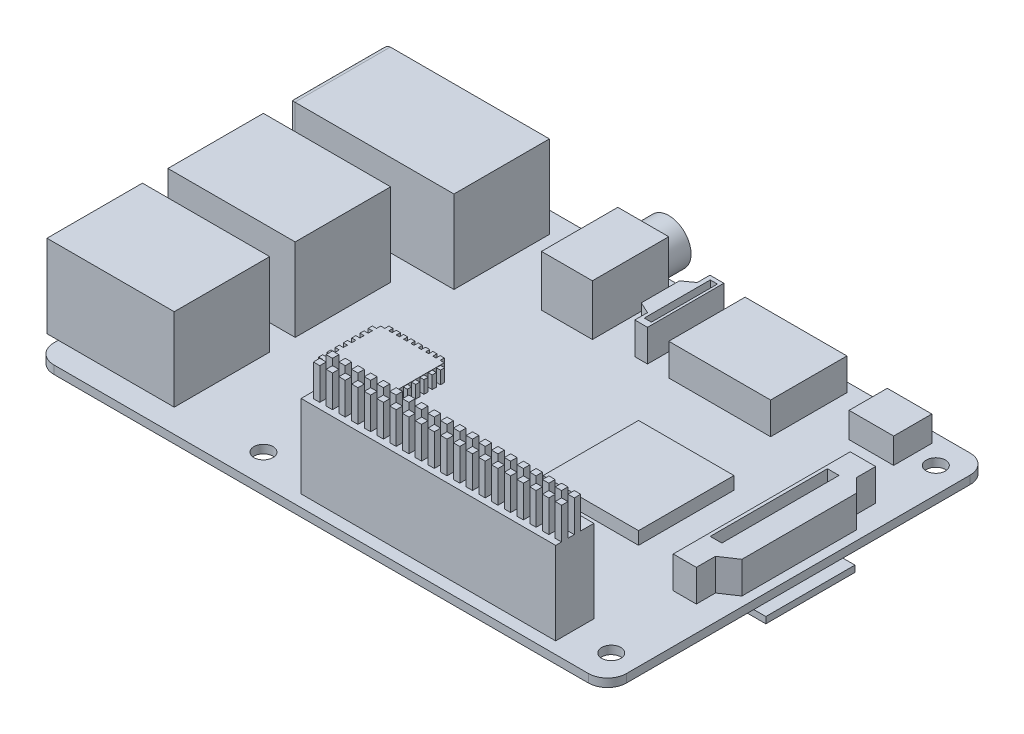
SolidWorks part; units mm, degrees
ref_plane "Front Plane" through (0, 0, 0) normal (0, 0, 1) x (1, 0, 0)
ref_plane "Top Plane" through (0, 0, 0) normal (0, 1, 0) x (1, 0, 0)
ref_plane "Right Plane" through (0, 0, 0) normal (1, 0, 0) x (0, 0, -1)
sketch "Sketch1" plane through (0, 0, 0) normal (0, 1, 0) x (1, 0, 0)
  line L1 (3, 0) -> (87, 0)
  line L2 (0, -3) -> (0, -57)
  line L3 (3, -60) -> (87, -60)
  line L4 (90, -3) -> (90, -57)
  line L6 (90, -18.75) -> (90, -31.25)
  arc A0 (87, 0) -> (90, -3) centre (87, -3) cw
  arc A1 (3, 0) -> (0, -3) centre (3, -3) ccw
  arc A2 (0, -57) -> (3, -60) centre (3, -57) ccw
  arc A3 (87, -60) -> (90, -57) centre (87, -57) ccw
  circle A4 centre (86, -55.4) radius 1.5
  circle A5 centre (86, -4.3927) radius 1.5
  circle A6 centre (31.3402, -55.4) radius 1.5
  circle A8 centre (31.3402, -4.3927) radius 1.5
  point P7 (90, 0)
  point P10 (0, 0)
  point P13 (0, -60)
  dimension "D3" = 3
  dimension "D4" = 3
  dimension "D5" = 1.6
  dimension "D6" = 4
  dimension "D7" = 4
  dimension "D8" = 3
  dimension "D1" = 90
  dimension "D2" = 60
extrude "Boss-Extrude3" add sketch "Sketch1" along normal blind 1.3 contours L3 A3 L4 A0 L1 A1 L2 A2
sketch "Sketch3" plane through (0, 0, 0) normal (0, -1, 0) x (1, 0, 0)
  line L6 (91.8941, 37) -> (71.8941, 37)
  line L7 (91.8941, 37) -> (91.8941, 23)
  line L8 (91.8941, 23) -> (71.8941, 23)
  line L9 (71.8941, 37) -> (71.8941, 23)
  arc A0 (87, 0) -> (90, 3) centre (87, 3) ccw construction
  arc A1 (90, 57) -> (87, 60) centre (87, 57) ccw construction
  dimension "D4" = 20
  dimension "D1" = 14
  dimension "D2" = 20
  dimension "2.1" = 20
extrude "Boss-Extrude4" add sketch "Sketch3" along normal blind 1
sketch "Sketch5" plane through (0, 1.3, 0) normal (0, 1, 0) x (1, 0, 0)
  line L1 (79.9977, -52.1364) -> (39.9977, -52.1364)
  line L2 (79.9977, -52.1364) -> (79.9977, -58.1364)
  line L3 (79.9977, -58.1364) -> (39.9977, -58.1364)
  line L4 (39.9977, -52.1364) -> (39.9977, -58.1364)
  dimension "D1" = 40
  dimension "D2" = 6
extrude "Boss-Extrude6" add sketch "Sketch5" along normal blind 13 contours L2 L3 L4 L1
sketch "Sketch9" plane through (0, 1.3, 0) normal (0, 1, 0) x (1, 0, 0)
  line L1 (18.2207, -41.3014) -> (-1.7793, -41.3014)
  line L2 (18.2207, -41.3014) -> (18.2207, -56.3014)
  line L3 (18.2207, -56.3014) -> (-1.7793, -56.3014)
  line L4 (-1.7793, -41.3014) -> (-1.7793, -56.3014)
  dimension "D1" = 15
  dimension "D2" = 20
extrude "Boss-Extrude7" add sketch "Sketch9" along normal blind 13
sketch "Sketch10" plane through (0, 1.3, 0) normal (0, 1, 0) x (1, 0, 0)
  line L1 (18.2251, -22.3014) -> (-1.7749, -22.3014)
  line L2 (18.2251, -22.3014) -> (18.2251, -37.3014)
  line L3 (18.2251, -37.3014) -> (-1.7749, -37.3014)
  line L4 (-1.7749, -22.3014) -> (-1.7749, -37.3014)
  dimension "D1" = 15
  dimension "D2" = 20
  dimension "D3" = 4
extrude "Boss-Extrude8" add sketch "Sketch10" along normal blind 13
sketch "Sketch12" plane through (0, 1.3, 0) normal (0, 1, 0) x (1, 0, 0)
  line L1 (24.1806, -3.3017) -> (-1.8194, -3.3017)
  line L2 (24.1806, -3.3017) -> (24.1806, -18.3017)
  line L3 (24.1806, -18.3017) -> (-1.8194, -18.3017)
  line L4 (-1.8194, -3.3017) -> (-1.8194, -18.3017)
  dimension "D1" = 15
  dimension "D2" = 26
  dimension "D3" = 4
extrude "Boss-Extrude9" add sketch "Sketch12" along normal blind 13
sketch "Sketch13" plane through (0, 1.3, 0) normal (0, 1, 0) x (1, 0, 0)
  line L1 (35.3901, -31.0333) -> (25.3901, -31.0333)
  line L2 (35.3901, -31.0333) -> (35.3901, -41.0333)
  line L3 (35.3901, -41.0333) -> (25.3901, -41.0333)
  line L4 (25.3901, -31.0333) -> (25.3901, -41.0333)
  dimension "D1" = 10
  dimension "D2" = 10
extrude "Boss-Extrude10" add sketch "Sketch13" along normal blind 2
sketch "Sketch14" plane through (0, 1.3, 0) normal (0, 1, 0) x (1, 0, 0)
  line L1 (73.5027, -23.6167) -> (58.5027, -23.6167)
  line L2 (73.5027, -23.6167) -> (73.5027, -38.6167)
  line L3 (73.5027, -38.6167) -> (58.5027, -38.6167)
  line L4 (58.5027, -23.6167) -> (58.5027, -38.6167)
  dimension "D1" = 15
  dimension "D2" = 15
extrude "Boss-Extrude11" add sketch "Sketch14" along normal blind 2
sketch "Sketch15" plane through (0, 1.3, 0) normal (0, 1, 0) x (1, 0, 0)
  line L1 (41.8681, -2.2375) -> (33.8681, -2.2375)
  line L2 (41.8681, -2.2375) -> (41.8681, -14.2375)
  line L3 (41.8681, -14.2375) -> (33.8681, -14.2375)
  line L4 (33.8681, -2.2375) -> (33.8681, -14.2375)
  dimension "D1" = 8
  dimension "D2" = 12
extrude "Boss-Extrude12" add sketch "Sketch15" along normal blind 8
sketch "Sketch16" plane through (0, 0, 2.2375) normal (0, 0, -1) x (-1, 0, 0)
  circle A0 centre (-37.8804, 4.69) radius 3.5
extrude "Boss-Extrude13" add sketch "Sketch16" along normal blind 4
sketch "Sketch17" plane through (0, 1.3, 0) normal (0, 1, 0) x (1, 0, 0)
  line L1 (69.1, -1.4635) -> (53.1, -1.4635)
  line L2 (69.1, -1.4635) -> (69.1, -13.4635)
  line L3 (69.1, -13.4635) -> (53.1, -13.4635)
  line L4 (53.1, -1.4635) -> (53.1, -13.4635)
  dimension "D1" = 16
  dimension "D2" = 12
extrude "Boss-Extrude15" add sketch "Sketch17" along normal blind 5
sketch "Sketch18" plane through (0, 1.3, 0) normal (0, 1, 0) x (1, 0, 0)
  line L1 (82.6732, -1.6952) -> (75.6732, -1.6952)
  line L2 (82.6732, -1.6952) -> (82.6732, -7.6952)
  line L3 (82.6732, -7.6952) -> (75.6732, -7.6952)
  line L4 (75.6732, -1.6952) -> (75.6732, -7.6952)
  dimension "D1" = 6
  dimension "D2" = 7
extrude "Boss-Extrude16" add sketch "Sketch18" along normal blind 4
fillet "Fillet1" radius 1 4 edges at (-1.8194, 7.8, 3.3017) (-1.8194, 14.3, 10.8017) (-1.8194, 7.8, 18.3017) (-1.8194, 1.3, 10.8017)
sketch "Sketch23" plane through (-1.8194, 0, 0) normal (-1, 0, 0) x (0, 0, 1)
  line L0 (8.563, 2.79) -> (13.2677, 2.79)
  line L1 (13.2677, 2.79) -> (13.2677, 4.6719)
  line L2 (13.2677, 4.6719) -> (13.2412, 5.2201)
  line L3 (13.2412, 5.2201) -> (15.1231, 5.2201)
  line L4 (15.1231, 5.2201) -> (15.1231, 7.102)
  line L5 (15.1231, 7.102) -> (17.0049, 7.102)
  line L6 (17.0049, 7.102) -> (17.0049, 12.6895)
  line L7 (17.0049, 12.6895) -> (4.7993, 12.6895)
  line L8 (4.7993, 12.6895) -> (4.7993, 6.925)
  line L9 (4.7993, 6.925) -> (6.6811, 6.925)
  line L10 (6.6811, 5.0431) -> (6.6811, 6.925)
  line L11 (8.563, 5.0431) -> (6.6811, 5.0431)
  line L12 (8.563, 5.0431) -> (8.563, 2.79)
  dimension "D1" = 4.7047
  dimension "D2" = 1.8819
  dimension "D3" = 1.8819
  dimension "D4" = 1.8819
  dimension "D5" = 1.8819
  dimension "D6" = 1.8819
  dimension "D9" = 1.8819
extrude "Cut-Extrude3" cut sketch "Sketch23" against normal blind 23
sketch "Sketch24" plane through (-1.7749, 0, 0) normal (-1, 0, 0) x (0, 0, 1)
  line L1 (23.5172, 13.3456) -> (35.907, 13.3456)
  line L2 (23.5172, 13.3456) -> (23.5172, 8.9047)
  line L3 (23.5172, 8.9047) -> (35.907, 8.9047)
  line L4 (35.907, 13.3456) -> (35.907, 8.9047)
  line L5 (23.5172, 13.3456) -> (35.907, 8.9047) construction
  line L6 (23.5172, 8.9047) -> (35.907, 13.3456) construction
  line L7 (23.5589, 2.1164) -> (35.9487, 2.1164)
  line L8 (23.5589, 2.1164) -> (23.5589, 6.5019)
  line L9 (23.5589, 6.5019) -> (35.9487, 6.5019)
  line L10 (35.9487, 2.1164) -> (35.9487, 6.5019)
  line L11 (23.5589, 2.1164) -> (35.9487, 6.5019) construction
  line L12 (23.5589, 6.5019) -> (35.9487, 2.1164) construction
  point P0 (29.7121, 11.1252)
  point P5 (29.7538, 4.3092)
extrude "Cut-Extrude4" cut sketch "Sketch24" against normal blind 18
sketch "Sketch25" plane through (16.2251, 0, 0) normal (-1, 0, 0) x (0, 0, 1)
  line L1 (25.109, 12.4996) -> (35.0042, 12.4996)
  line L2 (25.109, 12.4996) -> (25.109, 11.1096)
  line L3 (25.109, 11.1096) -> (35.0042, 11.1096)
  line L4 (35.0042, 12.4996) -> (35.0042, 11.1096)
  line L5 (25.109, 12.4996) -> (35.0042, 11.1096) construction
  line L6 (25.109, 11.1096) -> (35.0042, 12.4996) construction
  line L7 (24.8672, 5.4671) -> (35.3796, 5.4671)
  line L8 (24.8672, 5.4671) -> (24.8672, 4.135)
  line L9 (24.8672, 4.135) -> (35.3796, 4.135)
  line L10 (35.3796, 5.4671) -> (35.3796, 4.135)
  line L11 (24.8672, 5.4671) -> (35.3796, 4.135) construction
  line L12 (24.8672, 4.135) -> (35.3796, 5.4671) construction
  point P0 (30.0566, 11.8046)
  point P13 (30.1234, 4.801)
extrude "Boss-Extrude17" add sketch "Sketch25" along normal blind 16
sketch "Sketch27" plane through (-1.7793, 0, 0) normal (-1, 0, 0) x (0, 0, 1)
  line L1 (42.6441, 13.4236) -> (55.0441, 13.4236)
  line L2 (42.6441, 13.4236) -> (42.6441, 9.0236)
  line L3 (42.6441, 9.0236) -> (55.0441, 9.0236)
  line L4 (55.0441, 13.4236) -> (55.0441, 9.0236)
  line L5 (42.6441, 13.4236) -> (55.0441, 9.0236) construction
  line L6 (42.6441, 9.0236) -> (55.0441, 13.4236) construction
  point P0 (48.8441, 11.2236)
  dimension "D1" = 4.4
  dimension "D2" = 12.4
sketch "Sketch29" plane through (-1.7793, 0, 0) normal (-1, 0, 0) x (0, 0, 1)
  line L1 (42.6733, 6.7734) -> (55.0733, 6.7734)
  line L2 (42.6733, 6.7734) -> (42.6733, 2.3734)
  line L3 (42.6733, 2.3734) -> (55.0733, 2.3734)
  line L4 (55.0733, 6.7734) -> (55.0733, 2.3734)
  line L5 (42.6733, 6.7734) -> (55.0733, 2.3734) construction
  line L6 (42.6733, 2.3734) -> (55.0733, 6.7734) construction
  point P0 (48.8733, 4.5734)
  dimension "D1" = 4.4
  dimension "D2" = 12.4
extrude "Cut-Extrude5" cut sketch "Sketch27" against normal blind 16
extrude "Cut-Extrude6" cut sketch "Sketch29" against normal blind 16
sketch "Sketch30" plane through (14.2207, 0, 0) normal (-1, 0, 0) x (0, 0, 1)
  line L1 (53.6502, 12.6274) -> (43.6502, 12.6274)
  line L2 (53.6502, 12.6274) -> (53.6502, 11.4274)
  line L3 (53.6502, 11.4274) -> (43.6502, 11.4274)
  line L4 (43.6502, 12.6274) -> (43.6502, 11.4274)
  line L5 (53.6502, 12.6274) -> (43.6502, 11.4274) construction
  line L6 (53.6502, 11.4274) -> (43.6502, 12.6274) construction
  line L7 (53.6502, 5.7165) -> (43.6502, 5.7165)
  line L8 (53.6502, 5.7165) -> (53.6502, 4.5165)
  line L9 (53.6502, 4.5165) -> (43.6502, 4.5165)
  line L10 (43.6502, 5.7165) -> (43.6502, 4.5165)
  line L11 (53.6502, 5.7165) -> (43.6502, 4.5165) construction
  line L12 (53.6502, 4.5165) -> (43.6502, 5.7165) construction
  point P0 (48.6502, 12.0274)
  point P8 (48.6502, 5.1165)
  dimension "D1" = 1.2
  dimension "D2" = 1.2
  dimension "D3" = 10
  dimension "D4" = 10
extrude "Boss-Extrude21" add sketch "Sketch30" along normal blind 15
sketch "Sketch31" plane through (0, 14.3, 0) normal (0, 1, 0) x (1, 0, 0)
  line L0 (39.9977, -52.1364) -> (39.9977, -58.1364) construction
  line L1 (40.9977, -56.2076) -> (41.9977, -56.2076)
  line L2 (40.9977, -56.2076) -> (40.9977, -57.2076)
  line L3 (40.9977, -57.2076) -> (41.9977, -57.2076)
  line L4 (41.9977, -56.2076) -> (41.9977, -57.2076)
  line L5 (40.9977, -56.2076) -> (41.9977, -57.2076) construction
  line L6 (40.9977, -57.2076) -> (41.9977, -56.2076) construction
  line L8 (43.9977, -56.2076) -> (43.9977, -57.2076)
  line L9 (42.9977, -56.2076) -> (42.9977, -57.2076)
  line L10 (42.9977, -57.2076) -> (43.9977, -57.2076)
  line L11 (42.9977, -56.2076) -> (43.9977, -56.2076)
  line L12 (45.9977, -56.2076) -> (45.9977, -57.2076)
  line L13 (44.9977, -56.2076) -> (44.9977, -57.2076)
  line L14 (44.9977, -57.2076) -> (45.9977, -57.2076)
  line L15 (44.9977, -56.2076) -> (45.9977, -56.2076)
  line L16 (47.9977, -56.2076) -> (47.9977, -57.2076)
  line L17 (46.9977, -56.2076) -> (46.9977, -57.2076)
  line L18 (46.9977, -57.2076) -> (47.9977, -57.2076)
  line L19 (46.9977, -56.2076) -> (47.9977, -56.2076)
  line L20 (49.9977, -56.2076) -> (49.9977, -57.2076)
  line L21 (48.9977, -56.2076) -> (48.9977, -57.2076)
  line L22 (48.9977, -57.2076) -> (49.9977, -57.2076)
  line L23 (48.9977, -56.2076) -> (49.9977, -56.2076)
  line L24 (51.9977, -56.2076) -> (51.9977, -57.2076)
  line L25 (50.9977, -56.2076) -> (50.9977, -57.2076)
  line L26 (50.9977, -57.2076) -> (51.9977, -57.2076)
  line L27 (50.9977, -56.2076) -> (51.9977, -56.2076)
  line L28 (53.9977, -56.2076) -> (53.9977, -57.2076)
  line L29 (52.9977, -56.2076) -> (52.9977, -57.2076)
  line L30 (52.9977, -57.2076) -> (53.9977, -57.2076)
  line L31 (52.9977, -56.2076) -> (53.9977, -56.2076)
  line L32 (55.9977, -56.2076) -> (55.9977, -57.2076)
  line L33 (54.9977, -56.2076) -> (54.9977, -57.2076)
  line L34 (54.9977, -57.2076) -> (55.9977, -57.2076)
  line L35 (54.9977, -56.2076) -> (55.9977, -56.2076)
  line L36 (57.9977, -56.2076) -> (57.9977, -57.2076)
  line L37 (56.9977, -56.2076) -> (56.9977, -57.2076)
  line L38 (56.9977, -57.2076) -> (57.9977, -57.2076)
  line L39 (56.9977, -56.2076) -> (57.9977, -56.2076)
  line L40 (59.9977, -56.2076) -> (59.9977, -57.2076)
  line L41 (58.9977, -56.2076) -> (58.9977, -57.2076)
  line L42 (58.9977, -57.2076) -> (59.9977, -57.2076)
  line L43 (58.9977, -56.2076) -> (59.9977, -56.2076)
  line L44 (61.9977, -56.2076) -> (61.9977, -57.2076)
  line L45 (60.9977, -56.2076) -> (60.9977, -57.2076)
  line L46 (60.9977, -57.2076) -> (61.9977, -57.2076)
  line L47 (60.9977, -56.2076) -> (61.9977, -56.2076)
  line L48 (63.9977, -56.2076) -> (63.9977, -57.2076)
  line L49 (62.9977, -56.2076) -> (62.9977, -57.2076)
  line L50 (62.9977, -57.2076) -> (63.9977, -57.2076)
  line L51 (62.9977, -56.2076) -> (63.9977, -56.2076)
  line L52 (65.9977, -56.2076) -> (65.9977, -57.2076)
  line L53 (64.9977, -56.2076) -> (64.9977, -57.2076)
  line L54 (64.9977, -57.2076) -> (65.9977, -57.2076)
  line L55 (64.9977, -56.2076) -> (65.9977, -56.2076)
  line L56 (67.9977, -56.2076) -> (67.9977, -57.2076)
  line L57 (66.9977, -56.2076) -> (66.9977, -57.2076)
  line L58 (66.9977, -57.2076) -> (67.9977, -57.2076)
  line L59 (66.9977, -56.2076) -> (67.9977, -56.2076)
  line L60 (69.9977, -56.2076) -> (69.9977, -57.2076)
  line L61 (68.9977, -56.2076) -> (68.9977, -57.2076)
  line L62 (68.9977, -57.2076) -> (69.9977, -57.2076)
  line L63 (68.9977, -56.2076) -> (69.9977, -56.2076)
  line L64 (71.9977, -56.2076) -> (71.9977, -57.2076)
  line L65 (70.9977, -56.2076) -> (70.9977, -57.2076)
  line L66 (70.9977, -57.2076) -> (71.9977, -57.2076)
  line L67 (70.9977, -56.2076) -> (71.9977, -56.2076)
  line L68 (73.9977, -56.2076) -> (73.9977, -57.2076)
  line L69 (72.9977, -56.2076) -> (72.9977, -57.2076)
  line L70 (72.9977, -57.2076) -> (73.9977, -57.2076)
  line L71 (72.9977, -56.2076) -> (73.9977, -56.2076)
  line L72 (75.9977, -56.2076) -> (75.9977, -57.2076)
  line L73 (74.9977, -56.2076) -> (74.9977, -57.2076)
  line L74 (74.9977, -57.2076) -> (75.9977, -57.2076)
  line L75 (74.9977, -56.2076) -> (75.9977, -56.2076)
  line L76 (77.9977, -56.2076) -> (77.9977, -57.2076)
  line L77 (76.9977, -56.2076) -> (76.9977, -57.2076)
  line L78 (76.9977, -57.2076) -> (77.9977, -57.2076)
  line L79 (76.9977, -56.2076) -> (77.9977, -56.2076)
  line L80 (79.9977, -56.2076) -> (79.9977, -57.2076)
  line L81 (78.9977, -56.2076) -> (78.9977, -57.2076)
  line L82 (78.9977, -57.2076) -> (79.9977, -57.2076)
  line L83 (78.9977, -56.2076) -> (79.9977, -56.2076)
  line L84 (43.9977, -54.2076) -> (43.9977, -55.2076)
  line L85 (42.9977, -54.2076) -> (42.9977, -55.2076)
  line L86 (42.9977, -55.2076) -> (43.9977, -55.2076)
  line L87 (42.9977, -54.2076) -> (43.9977, -54.2076)
  line L88 (45.9977, -54.2076) -> (45.9977, -55.2076)
  line L89 (44.9977, -54.2076) -> (44.9977, -55.2076)
  line L90 (44.9977, -55.2076) -> (45.9977, -55.2076)
  line L91 (44.9977, -54.2076) -> (45.9977, -54.2076)
  line L92 (47.9977, -54.2076) -> (47.9977, -55.2076)
  line L93 (46.9977, -54.2076) -> (46.9977, -55.2076)
  line L94 (46.9977, -55.2076) -> (47.9977, -55.2076)
  line L95 (46.9977, -54.2076) -> (47.9977, -54.2076)
  line L96 (49.9977, -54.2076) -> (49.9977, -55.2076)
  line L97 (48.9977, -54.2076) -> (48.9977, -55.2076)
  line L98 (48.9977, -55.2076) -> (49.9977, -55.2076)
  line L99 (48.9977, -54.2076) -> (49.9977, -54.2076)
  line L100 (51.9977, -54.2076) -> (51.9977, -55.2076)
  line L101 (50.9977, -54.2076) -> (50.9977, -55.2076)
  line L102 (50.9977, -55.2076) -> (51.9977, -55.2076)
  line L103 (50.9977, -54.2076) -> (51.9977, -54.2076)
  line L104 (53.9977, -54.2076) -> (53.9977, -55.2076)
  line L105 (52.9977, -54.2076) -> (52.9977, -55.2076)
  line L106 (52.9977, -55.2076) -> (53.9977, -55.2076)
  line L107 (52.9977, -54.2076) -> (53.9977, -54.2076)
  line L108 (55.9977, -54.2076) -> (55.9977, -55.2076)
  line L109 (54.9977, -54.2076) -> (54.9977, -55.2076)
  line L110 (54.9977, -55.2076) -> (55.9977, -55.2076)
  line L111 (54.9977, -54.2076) -> (55.9977, -54.2076)
  line L112 (57.9977, -54.2076) -> (57.9977, -55.2076)
  line L113 (56.9977, -54.2076) -> (56.9977, -55.2076)
  line L114 (56.9977, -55.2076) -> (57.9977, -55.2076)
  line L115 (56.9977, -54.2076) -> (57.9977, -54.2076)
  line L116 (59.9977, -54.2076) -> (59.9977, -55.2076)
  line L117 (58.9977, -54.2076) -> (58.9977, -55.2076)
  line L118 (58.9977, -55.2076) -> (59.9977, -55.2076)
  line L119 (58.9977, -54.2076) -> (59.9977, -54.2076)
  line L120 (61.9977, -54.2076) -> (61.9977, -55.2076)
  line L121 (60.9977, -54.2076) -> (60.9977, -55.2076)
  line L122 (60.9977, -55.2076) -> (61.9977, -55.2076)
  line L123 (60.9977, -54.2076) -> (61.9977, -54.2076)
  line L124 (63.9977, -54.2076) -> (63.9977, -55.2076)
  line L125 (62.9977, -54.2076) -> (62.9977, -55.2076)
  line L126 (62.9977, -55.2076) -> (63.9977, -55.2076)
  line L127 (62.9977, -54.2076) -> (63.9977, -54.2076)
  line L128 (65.9977, -54.2076) -> (65.9977, -55.2076)
  line L129 (64.9977, -54.2076) -> (64.9977, -55.2076)
  line L130 (64.9977, -55.2076) -> (65.9977, -55.2076)
  line L131 (64.9977, -54.2076) -> (65.9977, -54.2076)
  line L132 (67.9977, -54.2076) -> (67.9977, -55.2076)
  line L133 (66.9977, -54.2076) -> (66.9977, -55.2076)
  line L134 (66.9977, -55.2076) -> (67.9977, -55.2076)
  line L135 (66.9977, -54.2076) -> (67.9977, -54.2076)
  line L136 (69.9977, -54.2076) -> (69.9977, -55.2076)
  line L137 (68.9977, -54.2076) -> (68.9977, -55.2076)
  line L138 (68.9977, -55.2076) -> (69.9977, -55.2076)
  line L139 (68.9977, -54.2076) -> (69.9977, -54.2076)
  line L140 (71.9977, -54.2076) -> (71.9977, -55.2076)
  line L141 (70.9977, -54.2076) -> (70.9977, -55.2076)
  line L142 (70.9977, -55.2076) -> (71.9977, -55.2076)
  line L143 (70.9977, -54.2076) -> (71.9977, -54.2076)
  line L144 (73.9977, -54.2076) -> (73.9977, -55.2076)
  line L145 (72.9977, -54.2076) -> (72.9977, -55.2076)
  line L146 (72.9977, -55.2076) -> (73.9977, -55.2076)
  line L147 (72.9977, -54.2076) -> (73.9977, -54.2076)
  line L148 (75.9977, -54.2076) -> (75.9977, -55.2076)
  line L149 (74.9977, -54.2076) -> (74.9977, -55.2076)
  line L150 (74.9977, -55.2076) -> (75.9977, -55.2076)
  line L151 (74.9977, -54.2076) -> (75.9977, -54.2076)
  line L152 (77.9977, -54.2076) -> (77.9977, -55.2076)
  line L153 (76.9977, -54.2076) -> (76.9977, -55.2076)
  line L154 (76.9977, -55.2076) -> (77.9977, -55.2076)
  line L155 (76.9977, -54.2076) -> (77.9977, -54.2076)
  line L156 (79.9977, -54.2076) -> (79.9977, -55.2076)
  line L157 (78.9977, -54.2076) -> (78.9977, -55.2076)
  line L158 (78.9977, -55.2076) -> (79.9977, -55.2076)
  line L159 (78.9977, -54.2076) -> (79.9977, -54.2076)
  line L160 (41.9977, -54.2076) -> (41.9977, -55.2076)
  line L161 (40.9977, -54.2076) -> (40.9977, -55.2076)
  line L162 (40.9977, -55.2076) -> (41.9977, -55.2076)
  line L163 (40.9977, -54.2076) -> (41.9977, -54.2076)
  point P0 (41.4977, -56.7076)
  dimension "D1" = 1
  dimension "D2" = 1
  dimension "D3" = 1
  dimension "D4" = 20
  dimension "D5" = 2
extrude "Boss-Extrude22" add sketch "Sketch31" along normal blind 5
sketch "Sketch32" plane through (0, 1.3, 0) normal (0, 1, 0) x (1, 0, 0)
  line L0 (88.5274, -19.3772) -> (88.5274, -37.3887)
  line L1 (88.5274, -19.3772) -> (86.4047, -17.2545)
  line L2 (86.4047, -17.2545) -> (86.4047, -14.2525)
  line L3 (86.4047, -14.2525) -> (82.4047, -14.2525)
  line L4 (82.4047, -14.2525) -> (82.4047, -42.0693)
  line L5 (82.4047, -42.0693) -> (86.0387, -42.0693)
  line L6 (86.0387, -42.0693) -> (86.0387, -39.0674)
  line L7 (86.0387, -39.0674) -> (88.5274, -37.3887)
  dimension "D1" = 18.0116
  dimension "D2" = 3.0019
  dimension "D3" = 3.0019
  dimension "D4" = 3.0019
  dimension "D5" = 4
  dimension "D6" = 3.0019
extrude "Boss-Extrude23" add sketch "Sketch32" along normal blind 5
sketch "Sketch33" plane through (0, 6.3, 0) normal (0, 1, 0) x (1, 0, 0)
  line L1 (84.7415, -18.343) -> (82.9156, -18.343)
  line L2 (84.7415, -18.343) -> (84.7415, -36.7655)
  line L3 (84.7415, -36.7655) -> (82.9156, -36.7655)
  line L4 (82.9156, -18.343) -> (82.9156, -36.7655)
  line L5 (84.7415, -18.343) -> (82.9156, -36.7655) construction
  line L6 (84.7415, -36.7655) -> (82.9156, -18.343) construction
  point P0 (83.8286, -27.5542)
extrude "Cut-Extrude7" cut sketch "Sketch33" against normal blind 5
sketch "Sketch34" plane through (0, 0, -1.7625) normal (0, 0, -1) x (-1, 0, 0)
  circle A0 centre (-37.7261, 4.82) radius 1.6
extrude "Cut-Extrude8" cut sketch "Sketch34" against normal blind 8
sketch "Sketch35" plane through (0, 0, 1.4635) normal (0, 0, -1) x (-1, 0, 0)
  line L0 (-66.445, 2.3109) -> (-56.445, 2.3109)
  line L2 (-54.6776, 3.4808) -> (-54.6776, 5.4808)
  line L3 (-54.6776, 5.4808) -> (-68.1222, 5.4808)
  line L4 (-68.1222, 5.4808) -> (-68.1222, 3.4978)
  line L6 (-68.1222, 3.4978) -> (-66.6222, 3.4978)
  line L7 (-66.6222, 3.4978) -> (-66.445, 2.3109)
  line L8 (-54.6776, 3.4808) -> (-56.1776, 3.4808)
  line L9 (-56.1776, 3.4808) -> (-56.445, 2.3109)
  dimension "D1" = 10
  dimension "D2" = 1.5
  dimension "D3" = 1.2
  dimension "D4" = 2
  dimension "D5" = 1.2
  dimension "D6" = 1.5
extrude "Cut-Extrude9" cut sketch "Sketch35" against normal blind 11
sketch "Sketch36" plane through (0, 0, 12.4635) normal (0, 0, -1) x (-1, 0, 0)
  line L1 (-67.471, 3.9039) -> (-56.3745, 3.9039)
  line L2 (-67.471, 3.9039) -> (-67.471, 4.8753)
  line L3 (-67.471, 4.8753) -> (-56.3745, 4.8753)
  line L4 (-56.3745, 3.9039) -> (-56.3745, 4.8753)
  line L5 (-67.471, 3.9039) -> (-56.3745, 4.8753) construction
  line L6 (-67.471, 4.8753) -> (-56.3745, 3.9039) construction
  point P0 (-61.9227, 4.3896)
extrude "Boss-Extrude24" add sketch "Sketch36" along normal blind 11
sketch "Sketch37" plane through (0, 0, 1.6952) normal (0, 0, -1) x (-1, 0, 0)
  line L0 (-81.3468, 4.5797) -> (-77.3346, 4.5797)
  line L1 (-77.3346, 4.5797) -> (-76.368, 3.6131)
  line L2 (-76.368, 3.6131) -> (-77.3346, 2.1365)
  line L3 (-77.3346, 2.1365) -> (-81.3468, 2.0338)
  line L4 (-81.3468, 2.0338) -> (-82.3235, 3.186)
  line L5 (-82.3235, 3.186) -> (-81.3468, 4.5797)
extrude "Cut-Extrude10" cut sketch "Sketch37" against normal blind 5
sketch "Sketch38" plane through (0, 0, 6.6952) normal (0, 0, -1) x (-1, 0, 0)
  line L1 (-81.0737, 3.83) -> (-77.9455, 3.83)
  line L2 (-81.0737, 3.83) -> (-81.0737, 4.2457)
  line L3 (-81.0737, 4.2457) -> (-77.9455, 4.2457)
  line L4 (-77.9455, 3.83) -> (-77.9455, 4.2457)
  line L5 (-81.0737, 3.83) -> (-77.9455, 4.2457) construction
  line L6 (-81.0737, 4.2457) -> (-77.9455, 3.83) construction
  point P0 (-79.5096, 4.0379)
extrude "Boss-Extrude25" add sketch "Sketch38" along normal blind 5
sketch "Sketch39" plane through (0, 3.3, 0) normal (0, 1, 0) x (1, 0, 0)
  line L0 (27.1901, -30.3833) -> (27.1901, -31.0333)
  line L5 (35.3901, -31.0333) -> (25.3901, -31.0333) construction
  line L6 (26.0401, -30.3833) -> (26.6901, -30.3833)
  line L7 (26.0401, -30.3833) -> (26.0401, -31.0333)
  line L8 (26.0401, -31.0333) -> (26.6901, -31.0333)
  line L9 (26.6901, -30.3833) -> (26.6901, -31.0333)
  line L10 (26.0401, -30.3833) -> (26.6901, -31.0333) construction
  line L11 (26.0401, -31.0333) -> (26.6901, -30.3833) construction
  line L12 (27.1901, -30.3833) -> (27.8401, -30.3833)
  line L13 (27.8401, -30.3833) -> (27.8401, -31.0333)
  line L14 (27.1901, -31.0333) -> (27.8401, -31.0333)
  line L15 (28.3401, -30.3833) -> (28.3401, -31.0333)
  line L16 (28.3401, -30.3833) -> (28.9901, -30.3833)
  line L17 (28.9901, -30.3833) -> (28.9901, -31.0333)
  line L18 (28.3401, -31.0333) -> (28.9901, -31.0333)
  line L19 (29.4901, -30.3833) -> (29.4901, -31.0333)
  line L20 (29.4901, -30.3833) -> (30.1401, -30.3833)
  line L21 (30.1401, -30.3833) -> (30.1401, -31.0333)
  line L22 (29.4901, -31.0333) -> (30.1401, -31.0333)
  line L23 (30.6401, -30.3833) -> (30.6401, -31.0333)
  line L24 (30.6401, -30.3833) -> (31.2901, -30.3833)
  line L25 (31.2901, -30.3833) -> (31.2901, -31.0333)
  line L26 (30.6401, -31.0333) -> (31.2901, -31.0333)
  line L27 (31.7901, -30.3833) -> (31.7901, -31.0333)
  line L28 (31.7901, -30.3833) -> (32.4401, -30.3833)
  line L29 (32.4401, -30.3833) -> (32.4401, -31.0333)
  line L30 (31.7901, -31.0333) -> (32.4401, -31.0333)
  line L31 (32.9401, -30.3833) -> (32.9401, -31.0333)
  line L32 (32.9401, -30.3833) -> (33.5901, -30.3833)
  line L33 (33.5901, -30.3833) -> (33.5901, -31.0333)
  line L34 (32.9401, -31.0333) -> (33.5901, -31.0333)
  line L35 (34.0901, -30.3833) -> (34.0901, -31.0333)
  line L36 (34.0901, -30.3833) -> (34.7401, -30.3833)
  line L37 (34.7401, -30.3833) -> (34.7401, -31.0333)
  line L38 (34.0901, -31.0333) -> (34.7401, -31.0333)
  line L39 (25.3901, -31.0333) -> (25.3901, -41.0333) construction
  line L44 (27.3398, -41.0526) -> (27.3398, -41.7026)
  line L45 (26.0398, -41.0526) -> (26.6898, -41.0526)
  line L46 (24.7401, -31.6833) -> (25.3901, -31.6833)
  line L47 (24.7401, -31.6833) -> (24.7401, -32.3333)
  line L48 (24.7401, -32.3333) -> (25.3901, -32.3333)
  line L49 (25.3901, -31.6833) -> (25.3901, -32.3333)
  line L50 (24.7401, -31.6833) -> (25.3901, -32.3333) construction
  line L51 (24.7401, -32.3333) -> (25.3901, -31.6833) construction
  line L52 (24.7401, -32.9833) -> (24.7401, -33.6333)
  line L53 (24.7401, -32.9833) -> (25.3901, -32.9833)
  line L54 (25.3901, -32.9833) -> (25.3901, -33.6333)
  line L55 (24.7401, -33.6333) -> (25.3901, -33.6333)
  line L56 (24.7401, -34.2833) -> (24.7401, -34.9333)
  line L57 (24.7401, -34.2833) -> (25.3901, -34.2833)
  line L58 (25.3901, -34.2833) -> (25.3901, -34.9333)
  line L59 (24.7401, -34.9333) -> (25.3901, -34.9333)
  line L60 (24.7401, -35.5833) -> (24.7401, -36.2333)
  line L61 (24.7401, -35.5833) -> (25.3901, -35.5833)
  line L62 (25.3901, -35.5833) -> (25.3901, -36.2333)
  line L63 (24.7401, -36.2333) -> (25.3901, -36.2333)
  line L64 (24.7401, -36.8833) -> (24.7401, -37.5333)
  line L65 (24.7401, -36.8833) -> (25.3901, -36.8833)
  line L66 (25.3901, -36.8833) -> (25.3901, -37.5333)
  line L67 (24.7401, -37.5333) -> (25.3901, -37.5333)
  line L68 (24.7401, -38.1833) -> (24.7401, -38.8333)
  line L69 (24.7401, -38.1833) -> (25.3901, -38.1833)
  line L70 (25.3901, -38.1833) -> (25.3901, -38.8333)
  line L71 (24.7401, -38.8333) -> (25.3901, -38.8333)
  line L72 (24.7401, -39.4833) -> (24.7401, -40.1333)
  line L73 (24.7401, -39.4833) -> (25.3901, -39.4833)
  line L74 (25.3901, -39.4833) -> (25.3901, -40.1333)
  line L75 (24.7401, -40.1333) -> (25.3901, -40.1333)
  line L76 (26.0398, -41.0526) -> (26.0398, -41.7026)
  line L77 (35.446, -31.6833) -> (36.096, -31.6833)
  line L78 (35.446, -31.6833) -> (35.446, -32.3333)
  line L79 (35.446, -32.3333) -> (36.096, -32.3333)
  line L80 (36.096, -31.6833) -> (36.096, -32.3333)
  line L81 (35.446, -31.6833) -> (36.096, -32.3333) construction
  line L82 (35.446, -32.3333) -> (36.096, -31.6833) construction
  line L83 (35.446, -32.9833) -> (35.446, -33.6333)
  line L84 (35.446, -32.9833) -> (36.096, -32.9833)
  line L85 (36.096, -32.9833) -> (36.096, -33.6333)
  line L86 (35.446, -33.6333) -> (36.096, -33.6333)
  line L87 (35.446, -34.2833) -> (35.446, -34.9333)
  line L88 (35.446, -34.2833) -> (36.096, -34.2833)
  line L89 (36.096, -34.2833) -> (36.096, -34.9333)
  line L90 (35.446, -34.9333) -> (36.096, -34.9333)
  line L91 (35.446, -35.5833) -> (35.446, -36.2333)
  line L92 (35.446, -35.5833) -> (36.096, -35.5833)
  line L93 (36.096, -35.5833) -> (36.096, -36.2333)
  line L94 (35.446, -36.2333) -> (36.096, -36.2333)
  line L95 (35.446, -36.8833) -> (35.446, -37.5333)
  line L96 (35.446, -36.8833) -> (36.096, -36.8833)
  line L97 (36.096, -36.8833) -> (36.096, -37.5333)
  line L98 (35.446, -37.5333) -> (36.096, -37.5333)
  line L99 (35.446, -38.1833) -> (35.446, -38.8333)
  line L100 (35.446, -38.1833) -> (36.096, -38.1833)
  line L101 (36.096, -38.1833) -> (36.096, -38.8333)
  line L102 (35.446, -38.8333) -> (36.096, -38.8333)
  line L103 (35.446, -39.4833) -> (35.446, -40.1333)
  line L104 (35.446, -39.4833) -> (36.096, -39.4833)
  line L105 (36.096, -39.4833) -> (36.096, -40.1333)
  line L106 (35.446, -40.1333) -> (36.096, -40.1333)
  line L107 (26.0398, -41.7026) -> (26.6898, -41.7026)
  line L108 (26.6898, -41.0526) -> (26.6898, -41.7026)
  line L109 (27.3398, -41.0526) -> (27.9898, -41.0526)
  line L110 (27.9898, -41.0526) -> (27.9898, -41.7026)
  line L111 (27.3398, -41.7026) -> (27.9898, -41.7026)
  line L112 (28.6398, -41.0526) -> (28.6398, -41.7026)
  line L113 (28.6398, -41.0526) -> (29.2898, -41.0526)
  line L114 (29.2898, -41.0526) -> (29.2898, -41.7026)
  line L115 (28.6398, -41.7026) -> (29.2898, -41.7026)
  line L116 (29.9398, -41.0526) -> (29.9398, -41.7026)
  line L117 (29.9398, -41.0526) -> (30.5898, -41.0526)
  line L118 (30.5898, -41.0526) -> (30.5898, -41.7026)
  line L119 (29.9398, -41.7026) -> (30.5898, -41.7026)
  line L120 (31.2398, -41.0526) -> (31.2398, -41.7026)
  line L121 (31.2398, -41.0526) -> (31.8898, -41.0526)
  line L122 (31.8898, -41.0526) -> (31.8898, -41.7026)
  line L123 (31.2398, -41.7026) -> (31.8898, -41.7026)
  line L124 (32.5398, -41.0526) -> (32.5398, -41.7026)
  line L125 (32.5398, -41.0526) -> (33.1898, -41.0526)
  line L126 (33.1898, -41.0526) -> (33.1898, -41.7026)
  line L127 (32.5398, -41.7026) -> (33.1898, -41.7026)
  line L128 (33.8398, -41.0526) -> (33.8398, -41.7026)
  line L129 (33.8398, -41.0526) -> (34.4898, -41.0526)
  line L130 (34.4898, -41.0526) -> (34.4898, -41.7026)
  line L131 (33.8398, -41.7026) -> (34.4898, -41.7026)
  point P0 (26.3651, -30.7083)
  point P43 (25.0651, -32.0083)
  point P49 (35.771, -32.0083)
  dimension "D1" = 0.65
  dimension "D2" = 0.65
  dimension "D3" = 0.65
  dimension "D5" = 0.65
  dimension "D6" = 0.65
  dimension "D7" = 0.65
  dimension "D8" = 0.65
  dimension "D10" = 0.65
  dimension "D11" = 0.65
  dimension "D12" = 0.65
  dimension "D13" = 90
  dimension "D14" = 0.65
  dimension "D16" = 0.65
  dimension "D17" = 0.65
  dimension "D18" = 0.65
  dimension "D19" = 0.65
  dimension "D21" = 0.9003
  dimension "0.065" = 0.65
  dimension "D4" = 8
  dimension "D9" = 7
  dimension "D15" = 7
  dimension "D20" = 7
extrude "Boss-Extrude27" add sketch "Sketch39" against normal up to surface (2 mm away)
sketch "Sketch40" plane through (0, 1.3, 0) normal (0, 1, 0) x (1, 0, 0)
  line L0 (49.5339, -1.2362) -> (49.5339, -13.2362)
  line L1 (49.5339, -13.2362) -> (47.5339, -13.2362)
  line L2 (47.5339, -13.2362) -> (47.5339, -11.2362)
  line L3 (47.5339, -11.2362) -> (45.7172, -10.3999)
  line L4 (45.7172, -10.3999) -> (45.7172, -4.3999)
  line L5 (45.7172, -4.3999) -> (47.3438, -3.2362)
  line L6 (47.3438, -3.2362) -> (47.3438, -1.2362)
  line L7 (47.3438, -1.2362) -> (49.5339, -1.2362)
  dimension "D1" = 12
  dimension "D2" = 2
  dimension "D3" = 2
  dimension "D4" = 2
  dimension "D5" = 6
  dimension "D6" = 2
  dimension "D7" = 2
extrude "Boss-Extrude28" add sketch "Sketch40" along normal blind 5
sketch "Sketch41" plane through (0, 6.3, 0) normal (0, 1, 0) x (1, 0, 0)
  line L1 (49.1412, -1.8579) -> (48.0176, -1.8579)
  line L2 (49.1412, -1.8579) -> (49.1412, -12.2362)
  line L3 (49.1412, -12.2362) -> (48.0176, -12.2362)
  line L4 (48.0176, -1.8579) -> (48.0176, -12.2362)
  line L5 (49.1412, -1.8579) -> (48.0176, -12.2362) construction
  line L6 (49.1412, -12.2362) -> (48.0176, -1.8579) construction
  point P0 (48.5794, -7.047)
extrude "Cut-Extrude11" cut sketch "Sketch41" against normal blind 4
sketch "Sketch42" plane through (0, 1.3, 0) normal (0, 1, 0) x (1, 0, 0)
  text T0 "Kelompok 11\r\n"
